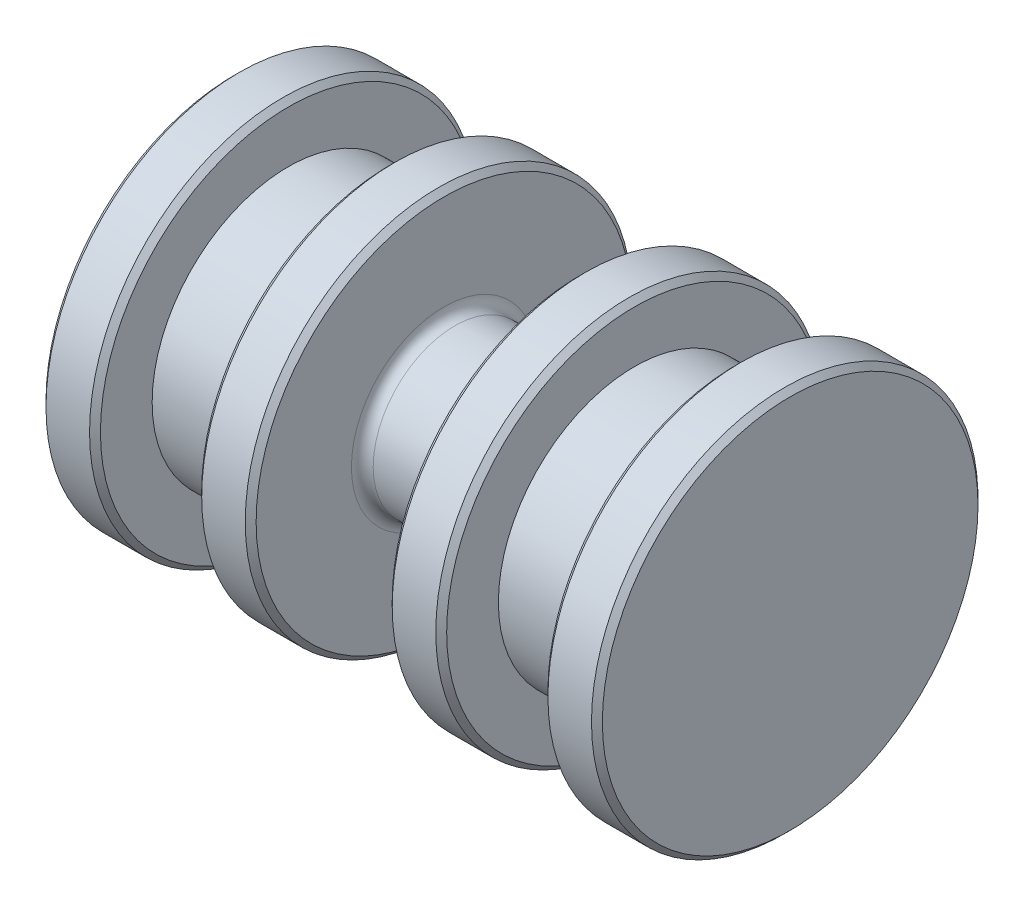
SolidWorks part; units mm, degrees
material "6063-T6"
ref_plane "Front Plane" through (0, 0, 0) normal (0, 0, 1) x (1, 0, 0)
ref_plane "Top Plane" through (0, 0, 0) normal (0, 1, 0) x (1, 0, 0)
ref_plane "Right Plane" through (0, 0, 0) normal (1, 0, 0) x (0, 0, -1)
sketch "Sketch1" plane through (0, 0, 0) normal (1, 0, 0) x (0, 0, -1)
  circle A0 centre (0, 0) radius 4.5085
  dimension "D1" = 9.017
sketch "Sketch2" plane through (0, 0, 0) normal (0, 0, 1) x (1, 0, 0)
  line L0 (-1.6174, 0) -> (23.3579, 0) construction
  line L2 (3.6322, 4.5085) -> (3.6322, 3.175)
  line L3 (3.6322, 3.175) -> (1.27, 3.175)
  line L4 (1.27, 3.175) -> (1.27, 4.5085)
  line L6 (12.9794, 5.6982) -> (12.9794, -5.5364) construction
  line L13 (11.7094, 4.5085) -> (11.7094, 3.175)
  line L14 (11.7094, 3.175) -> (9.3472, 3.175)
  line L15 (9.3472, 3.175) -> (9.3472, 4.5085)
  line L16 (0, 0) -> (0, 4.5085)
  line L18 (4.9022, 4.5085) -> (4.9022, 1.905)
  line L19 (4.9022, 1.905) -> (8.0772, 1.905)
  line L20 (8.0772, 4.5085) -> (8.0772, 1.905)
  line L21 (0, -4.5085) -> (0, 4.5085) construction
  line L22 (0, 4.5085) -> (1.27, 4.5085)
  line L23 (3.6322, 4.5085) -> (4.9022, 4.5085)
  line L24 (8.0772, 4.5085) -> (9.3472, 4.5085)
  line L27 (12.9794, 0) -> (0, 0)
  line L31 (11.7094, 4.5085) -> (12.9794, 4.5085)
  line L33 (12.9794, 4.5085) -> (12.9794, 0)
  dimension "D2" = 6.35
  dimension "D3" = 2.3622
  dimension "D4" = 1.27
  dimension "D5" = 1.27
  dimension "D6" = 2.3622
  dimension "D7" = 3.175
  dimension "D8" = 9.017
  dimension "D10" = 3.81
sketch "Sketch3" [suppressed] plane through (22.86, 0, 0) normal (1, 0, 0) x (0, 0, -1)
  circle A0 centre (0, 0) radius 7.9117
revolve "Revolve1" add sketch "Sketch2" angle 360 about L0
chamfer "vent-edge-break" distance 0.127 angle 45 8 edges at (11.7094, 0, 4.5085) (12.9794, 0, 4.5085) (9.3472, 0, 4.5085) (8.0772, 0, 4.5085) (4.9022, 0, 4.5085) (3.6322, 0, 4.5085) (1.27, 0, 4.5085) (0, 0, 4.5085)
fillet "Fillet1" radius 0.254 2 edges at (8.0772, 0, 1.905) (4.9022, 0, 1.905)
